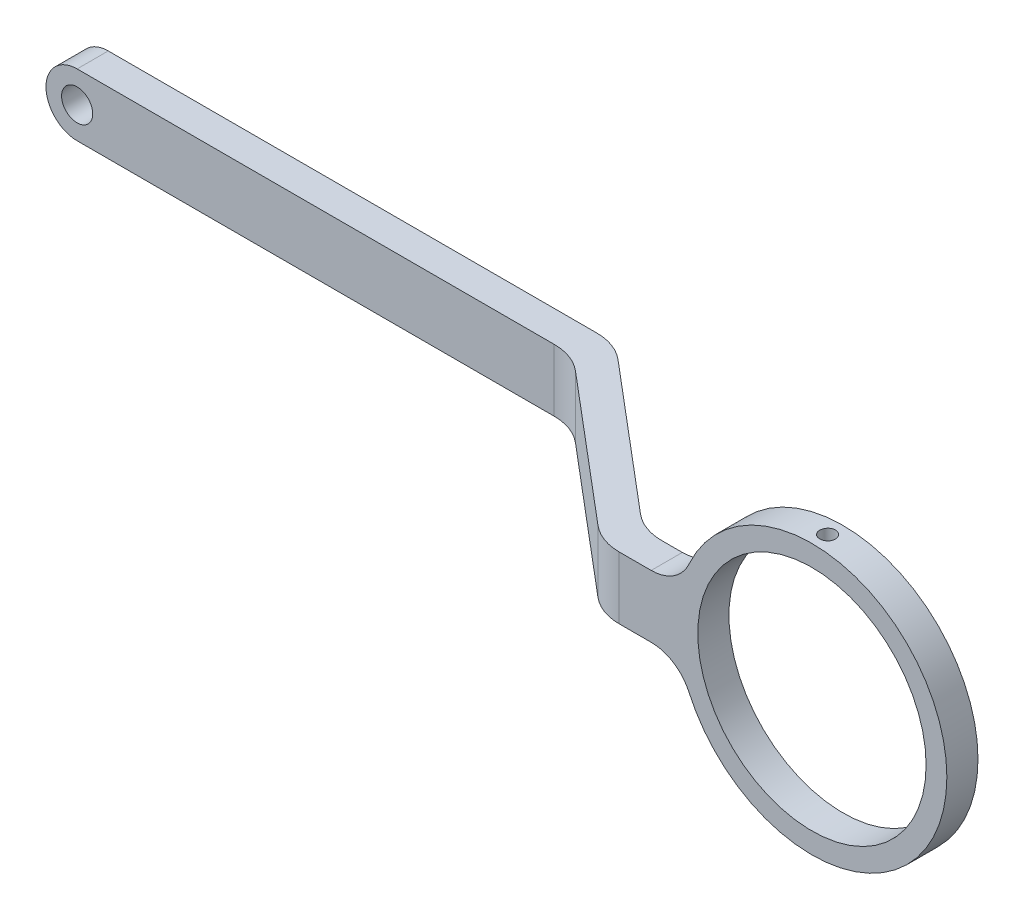
SolidWorks part; units mm, degrees
ref_plane "Front Plane" through (0, 0, 0) normal (0, 0, 1) x (1, 0, 0)
ref_plane "Top Plane" through (0, 0, 0) normal (0, 1, 0) x (1, 0, 0)
ref_plane "Right Plane" through (0, 0, 0) normal (1, 0, 0) x (0, 0, -1)
sketch "Sketch1" plane through (0, 0, 0) normal (0, 1, 0) x (1, 0, 0)
  line L0 (-645.16, 0) -> (645.16, 0) construction
  line L1 (638.2645, -37.6928) -> (638.2645, -368.2354) construction
  line L2 (638.2645, -368.2354) -> (1064.8291, -368.2354) construction
  line L3 (1092.8644, -322.0078) -> (1064.9845, -398.2078) construction
  line L4 (666.1444, 38.5072) -> (1092.8644, -322.0078)
  line L5 (-652.0555, -37.6928) -> (638.2645, -37.6928)
  line L6 (-652.0555, -37.6928) -> (-652.0555, 38.5072)
  line L7 (-652.0555, 38.5072) -> (666.1444, 38.5072)
  line L9 (-652.0555, -37.6928) -> (666.1444, 38.5072) construction
  line L10 (-652.0555, 38.5072) -> (638.2645, -37.6928) construction
  line L11 (1064.9845, -398.2078) -> (1913.3445, -398.2078)
  line L13 (1092.8644, -322.0078) -> (1913.3445, -322.0078)
  line L14 (1913.3445, -398.2078) -> (1913.3445, -322.0078)
  line L15 (1078.9245, -360.1078) -> (1913.3445, -360.1078) construction
  line L17 (638.2645, -37.6928) -> (1064.9845, -398.2078)
  point P4 (0, 0)
  point P9 (0, 0)
  point P15 (1501.8257, -368.2354)
  dimension "D3" = 76.2
  dimension "D1" = 1290.32
  dimension "D2" = 645.16
  dimension "D4" = 368.3
  dimension "D5" = 426.72
  dimension "D6" = 38.1
  dimension "D7" = 76.2
  dimension "D8" = 1290.32
  dimension "D9" = 38.1
  dimension "D10" = 848.36
extrude "Boss-Extrude1" add sketch "Sketch1" along normal mid plane 152.4
fillet "Fillet1" radius 127 4 edges at (1064.9845, 0, 398.2078) (1092.8644, 0, 322.0078) (666.1444, 0, -38.5072) (638.2645, 0, 37.6928)
sketch "Sketch3" plane through (0, 0, 37.6928) normal (0, 0, 1) x (1, 0, 0)
  line L0 (-652.0555, 76.2) -> (-652.0555, -76.2) construction
  line L1 (-575.8555, 76.2) -> (-652.0555, 76.2)
  line L2 (-652.0555, 76.2) -> (-652.0555, -76.2)
  line L3 (-652.0555, -76.2) -> (-575.8555, -76.2)
  arc A0 (-575.8555, 76.2) -> (-575.8555, -76.2) centre (-575.8555, 0) ccw
  point P2 (-652.0555, 0)
  point P3 (-652.0555, 0)
  line M1 (-652.0555, -76.2) -> (591.7981, -76.2)
  line M3 (591.7981, 76.2) -> (-652.0555, 76.2)
  line M4 (-652.0555, 76.2) -> (-652.0555, -76.2)
  dimension "D1" = 152.4
extrude "Cut-Extrude1" cut sketch "Sketch3" against normal blind 152.4 contours A0 M3 M4 | A0 L2 M1
sketch "Sketch4" plane through (0, 0, 37.6928) normal (0, 0, 1) x (1, 0, 0)
  line L0 (-575.8555, 76.2) -> (-575.8555, -76.2) construction
  circle A0 centre (-575.8555, 0) radius 38.1
  dimension "D1" = 76.2
extrude "Cut-Extrude2" cut sketch "Sketch4" against normal blind 152.4
sketch "Sketch5" plane through (0, 0, 398.2078) normal (0, 0, 1) x (1, 0, 0)
  line L0 (-575.8555, 0) -> (1583.1445, 0) construction
  circle A0 centre (1583.1445, 0) radius 279.4
  circle A1 centre (1583.1445, 0) radius 330.2
  dimension "D2" = 558.8
  dimension "D3" = 660.4
  dimension "D1" = 2159
extrude "Boss-Extrude2" add sketch "Sketch5" against normal blind 76.2
sketch "Sketch6" plane through (0, 0, 398.2078) normal (0, 0, 1) x (1, 0, 0)
  line L0 (1904.4319, 76.2) -> (1913.3445, 76.2)
  line L1 (1913.3445, 76.2) -> (1913.3445, -76.2)
  line L2 (1913.3445, -76.2) -> (1904.4319, -76.2)
  arc A0 (1904.4319, -76.2) -> (1904.4319, 76.2) centre (1583.1445, 0) ccw
  line M7 (1904.4319, -76.2) -> (1913.3445, -76.2)
  line M8 (1913.3445, -76.2) -> (1913.3445, 76.2)
  line M9 (1913.3445, 76.2) -> (1904.4319, 76.2)
extrude "Cut-Extrude3" cut sketch "Sketch6" against normal blind 76.2 contours A0 L1 M9 | A0 M7 M8
sketch "Sketch7" plane through (0, 0, 398.2078) normal (0, 0, 1) x (1, 0, 0)
  circle A0 centre (1583.1445, 0) radius 279.4
  dimension "D1" = 558.8
extrude "Cut-Extrude4" cut sketch "Sketch7" against normal blind 76.2
fillet "Fillet2" radius 101.6 2 edges at (1261.8571, -76.2, 360.1078) (1261.8571, 76.2, 360.1078)
sketch "Sketch9" plane through (0, 0, 37.6928) normal (0, 0, 1) x (1, 0, 0)
  line L0 (-575.8555, 0) -> (1583.1445, 0) construction
  line L1 (1583.1445, 0) -> (1583.1445, 330.2) construction
  arc A0 (1282.2365, -135.9647) -> (1282.2365, 135.9647) centre (1583.1445, 0) ccw construction
sketch "Sketch10" plane through (0, 0, 0) normal (0, 1, 0) x (1, 0, 0)
  line L0 (1583.1445, -37.6928) -> (1583.1445, -322.0078) construction
  line L2 (1282.2365, -398.2078) -> (1913.3445, -398.2078) construction
  line L3 (1583.1445, -398.2078) -> (1583.1445, -322.0078) construction
  line L4 (1862.5445, -322.0078) -> (1303.7445, -322.0078) construction
  line L5 (-575.8555, -37.6928) -> (1583.1445, -37.6928) construction
  circle A0 centre (1583.1445, -360.1078) radius 19.05
  dimension "D1" = 38.1
extrude "Cut-Extrude5" cut sketch "Sketch10" along normal through all
